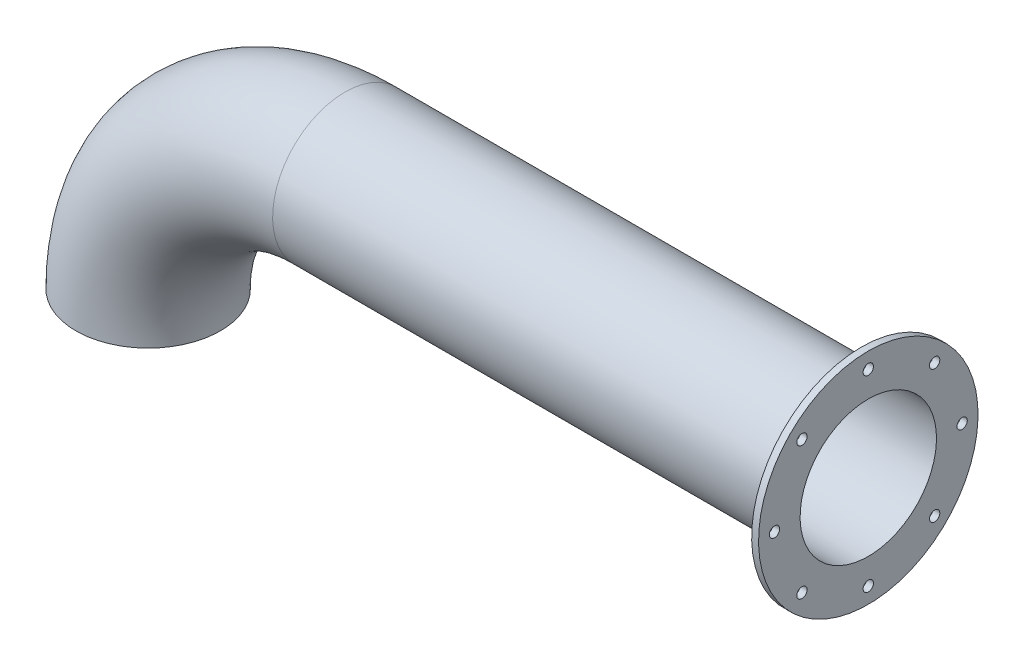
SolidWorks part; units mm, degrees
ref_plane "Front Plane" through (0, 0, 0) normal (0, 0, 1) x (1, 0, 0)
ref_plane "Top Plane" through (0, 0, 0) normal (0, 1, 0) x (1, 0, 0)
ref_plane "Right Plane" through (0, 0, 0) normal (1, 0, 0) x (0, 0, -1)
sketch "Sketch1" plane through (0, 0, 0) normal (0, 1, 0) x (1, 0, 0)
  circle A0 centre (0, 0) radius 79.22
  circle A1 centre (0, 0) radius 84
  dimension "D1" = 168
  dimension "D2" = 158.44
sketch "Sketch2" plane through (0, 0, 0) normal (0, 0, 1) x (1, 0, 0)
  line L0 (0, 0) -> (228.6, 0) construction
  line L1 (79.22, 0) -> (-79.22, 0) construction
  line L2 (228.6, 0) -> (228.6, 228.6) construction
  arc A0 (0, 0) -> (228.6, 228.6) centre (228.6, 0) cw
  dimension "D1" = 228.6
sweep "Sweep1" add profiles "Sketch1" path "Sketch2"
sketch "Sketch3" plane through (228.6, 0, 0) normal (1, 0, 0) x (0, 0, -1)
  circle A0 centre (0, 228.6) radius 79.22
  circle A1 centre (0, 228.6) radius 84
  circle A2 centre (0, 228.6) radius 84
  dimension "D1" = 0
extrude "Boss-Extrude1" add sketch "Sketch3" along normal blind 600
sketch "Sketch4" plane through (828.6, 0, 0) normal (1, 0, 0) x (0, 0, -1)
  line L0 (0, 228.6) -> (0, 337.6) construction
  circle A0 centre (0, 228.6) radius 127.5
  circle A1 centre (0, 228.6) radius 79.22
  circle A2 centre (0, 228.6) radius 109 construction
  circle A3 centre (0, 337.6) radius 6
  circle A4 centre (77.0746, 305.6746) radius 6
  circle A5 centre (109, 228.6) radius 6
  circle A6 centre (77.0746, 151.5254) radius 6
  circle A7 centre (0, 119.6) radius 6
  circle A8 centre (-77.0746, 151.5254) radius 6
  circle A9 centre (-109, 228.6) radius 6
  circle A10 centre (-77.0746, 305.6746) radius 6
  point P23 (0, 228.6)
  dimension "D1" = 218
  dimension "D2" = 255
  dimension "D3" = 12
  dimension "D4" = 8
extrude "Boss-Extrude2" add sketch "Sketch4" along normal blind 8
